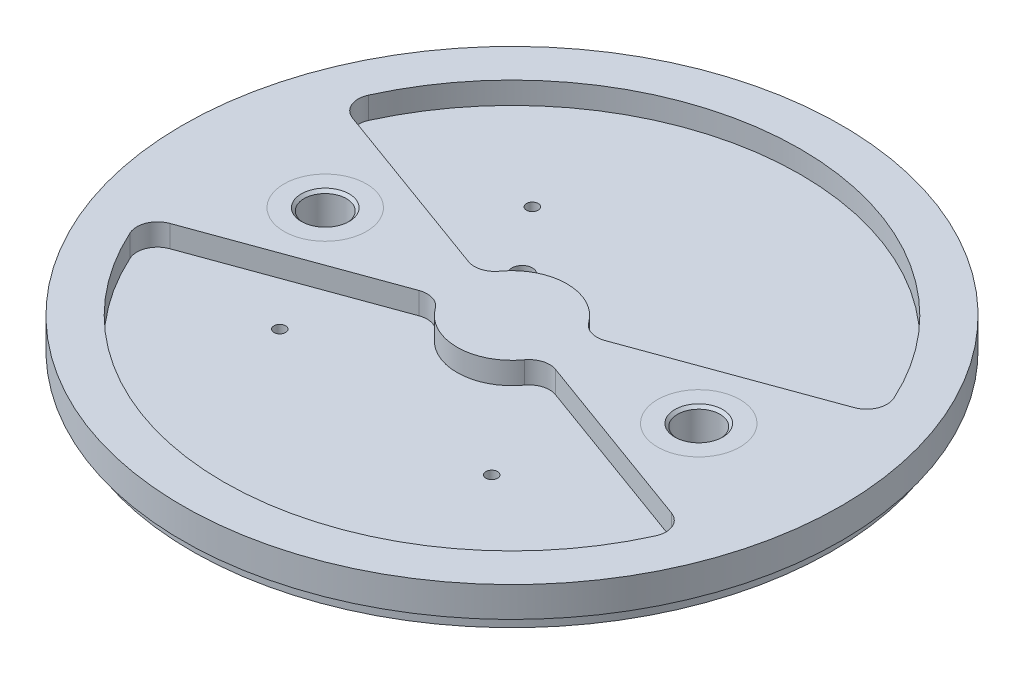
SolidWorks part; units mm, degrees
material "Delrin 2700 NC010, Low Viscosity Acetal Copolymer (SS)"
ref_plane "Front Plane" through (0, 0, 0) normal (0, 0, 1) x (1, 0, 0)
ref_plane "Top Plane" through (0, 0, 0) normal (0, 1, 0) x (1, 0, 0)
ref_plane "Right Plane" through (0, 0, 0) normal (1, 0, 0) x (0, 0, -1)
sketch "Sketch1" plane through (0, 0, 0) normal (0, 1, 0) x (1, 0, 0)
  circle A0 centre (0, 0) radius 76.2
  dimension "D1" = 152.4
extrude "Boss-Extrude1" add sketch "Sketch1" along normal blind 10.16
hole_wizard "Tap Drill for #4-40 Tap1" [suppressed] positions "Sketch3" profile "Sketch4" hole size "#4-40" standard "ANSI Inch"
sketch "Sketch3" plane through (0, 0, 0) normal (0, -1, 0) x (-1, 0, 0)
  point P0 (0, 25.4)
  point P2 (0, 50.4)
  dimension "D1" = 25.4
  dimension "D2" = 25
sketch "Sketch4" plane through (0, 0, -25.4) normal (1, 0, 0) x (0, 0, -1)
  line L0 (0, 0) -> (0, 10.16)
  line L1 (0, 10.16) -> (1.1303, 10.16)
  line L2 (1.1303, 10.16) -> (1.1303, 0)
  line L5 (1.1303, 0) -> (0, 0)
  line L11 (0, -6.35) -> (0, 107.95) construction
  dimension "Thru Hole Dia." = 2.2606
  dimension "Thru Hole Depth" = 10.16
sketch "Sketch2" [suppressed] plane through (0, 0, 0) normal (0, -1, 0) x (1, 0, 0)
  line L0 (0, 0) -> (0, -55.372) construction
  line L1 (-3.429, -27.686) -> (3.429, -27.686)
  line L2 (-5.969, -30.226) -> (-5.969, -45.574)
  line L3 (-3.429, -48.114) -> (3.429, -48.114)
  line L4 (5.969, -30.226) -> (5.969, -45.574)
  arc A0 (3.429, -48.114) -> (5.969, -45.574) centre (3.429, -45.574) ccw
  arc A1 (-5.969, -45.574) -> (-3.429, -48.114) centre (-3.429, -45.574) ccw
  arc A2 (3.429, -27.686) -> (5.969, -30.226) centre (3.429, -30.226) cw
  arc A3 (-3.429, -27.686) -> (-5.969, -30.226) centre (-3.429, -30.226) ccw
  circle A4 centre (0, -25.4) radius 1.1303 construction
  circle A5 centre (0, -50.4) radius 1.1303 construction
  point P10 (5.969, -27.686)
  point P13 (-5.969, -27.686)
  point P17 (0, -27.686)
  dimension "D2" = 2.54
  dimension "D1" = 11.938
  dimension "D3" = 2.286
  dimension "D4" = 2.286
extrude "Cut-Extrude1" [suppressed] cut sketch "Sketch2" against normal through all
hole_wizard "Tap Drill for #6-32 Tap1" positions "Sketch5" profile "Sketch6" hole size "#6-32" standard "ANSI Inch" end condition through all
sketch "Sketch5" plane through (0, 0, 0) normal (0, -1, 0) x (-1, 0, 0)
  line L0 (0, 0) -> (58.3519, 0) construction
  line L2 (0, 0) -> (37.5212, 6.616) construction
  point P0 (37.5212, 6.616)
  dimension "D1" = 10
  dimension "D2" = 38.1
sketch "Sketch6" plane through (-37.5212, 0, -6.616) normal (1, 0, 0) x (0, 0, -1)
  line L0 (0, 0) -> (0, 10.16)
  line L1 (0, 10.16) -> (1.3525, 10.16)
  line L2 (1.3525, 10.16) -> (1.3525, 0)
  line L5 (1.3525, 0) -> (0, 0)
  line L11 (0, -6.35) -> (0, 107.95) construction
  dimension "Thru Hole Dia." = 2.7051
  dimension "Thru Hole Depth" = 10.16
pattern_circular "CirPattern1" count 4 over 360 about axis through (0, 0, 0) along (0, 1, 0) skipping 3 of "Tap Drill for #6-32 Tap1"
hole_wizard "W (0.386) Diameter Hole1" positions "Sketch7" profile "Sketch8" hole size "W" standard "ANSI Inch" end condition through all
sketch "Sketch7" plane through (0, 0, 0) normal (0, -1, 0) x (-1, 0, 0)
  line L2 (0, 0) -> (-33.0778, 27.7556) construction
  line L4 (0, 0) -> (0, 19.4817) construction
  point P0 (-33.0778, 27.7556)
  point P17 (33.0778, -27.7556)
  dimension "D1" = 50
  dimension "D2" = 43.18
  dimension "D3" = 43.18
sketch "Sketch8" plane through (33.0778, 0, -27.7556) normal (1, 0, 0) x (0, 0, -1)
  line L0 (0, 0) -> (0, 10.16)
  line L1 (0, 10.16) -> (4.9022, 10.16)
  line L2 (4.9022, 10.16) -> (4.9022, 0)
  line L5 (4.9022, 0) -> (0, 0)
  line L11 (0, -6.35) -> (0, 107.95) construction
  dimension "Thru Hole Dia." = 9.8044
  dimension "Thru Hole Depth" = 10.16
hole_wizard "3/16 (0.1875) Diameter Hole1" positions "Sketch10" profile "Sketch11" hole size "3/16" standard "ANSI Inch" end condition through all
sketch "Sketch10" plane through (0, 0, 0) normal (0, -1, 0) x (-1, 0, 0)
  line L0 (0, 0) -> (37.5212, 6.616) construction
  point P0 (18.7606, 3.308)
sketch "Sketch11" plane through (-18.7606, 0, -3.308) normal (1, 0, 0) x (0, 0, -1)
  line L0 (0, 0) -> (0, 10.16)
  line L1 (0, 10.16) -> (2.3812, 10.16)
  line L2 (2.3812, 10.16) -> (2.3812, 0)
  line L5 (2.3812, 0) -> (0, 0)
  line L11 (0, -6.35) -> (0, 107.95) construction
  dimension "Thru Hole Dia." = 4.7625
  dimension "Thru Hole Depth" = 10.16
sketch "Sketch12" plane through (0, 0, 0) normal (0, -1, 0) x (1, 0, 0)
  line L0 (0, 0) -> (31.6547, 37.7246) construction
  line L10 (19.8869, 28.7385) -> (24.8486, 24.5751)
  line L11 (19.8869, 28.7385) -> (6.4989, 12.7833)
  line L12 (6.4989, 12.7833) -> (11.4606, 8.62)
  line L13 (24.8486, 24.5751) -> (11.4606, 8.62)
  line L17 (0, 0) -> (-53.1972, 0) construction
  line L18 (-33.0778, 27.7556) -> (33.0778, -27.7556) construction
  circle A0 centre (22.3677, 26.6568) radius 3.2385
  circle A1 centre (8.9797, 10.7016) radius 3.2385
  circle A2 centre (33.0778, -27.7556) radius 4.9022 construction
  circle A3 centre (-33.0778, 27.7556) radius 4.9022 construction
  circle A4 centre (33.0778, -27.7556) radius 4.9022
  circle A5 centre (-33.0778, 27.7556) radius 4.9022
  dimension "D1" = 6.477
  dimension "D2" = 13.97
  dimension "D3" = 20.828
extrude "Cut-Extrude4" cut sketch "Sketch12" against normal blind 3.175 contours A1 L13 A0 L11 | L10 A0 | L12 A1 | L12 A1 | L10 A0
ref_plane "Plane1" through (0, 0, 0) normal (0.6428, 0, 0.766) x (0.766, 0, -0.6428)
mirror "Mirror1" about plane through (0, 0, 0) normal (0.6428, 0, 0.766) of "Cut-Extrude4"
sketch "Sketch15" plane through (0, 0, 0) normal (0, -1, 0) x (1, 0, 0)
  circle A0 centre (0, 0) radius 74.041
  circle A1 centre (0, 0) radius 76.2 construction
  circle A2 centre (0, 0) radius 76.2
  dimension "D1" = 148.082
extrude "Cut-Extrude5" cut sketch "Sketch15" against normal blind 3.175
sketch "Sketch17" plane through (0, 10.16, 0) normal (0, 1, 0) x (1, 0, 0)
  circle A0 centre (-33.0778, -27.7556) radius 9.525
  circle A1 centre (33.0778, 27.7556) radius 9.525
  dimension "D1" = 19.05
  dimension "D2" = 19.05
split line "Split Line1"
sketch "Sketch19" plane through (0, 0, 0) normal (0, -1, 0) x (1, 0, 0)
  circle A0 centre (-33.0778, 27.7556) radius 9.525
  circle A1 centre (33.0778, -27.7556) radius 9.525
  dimension "D1" = 19.05
  dimension "D2" = 19.05
split line "Split Line2"
sketch "Sketch18" plane through (0, 10.16, 0) normal (0, 1, 0) x (1, 0, 0)
  circle A0 centre (0, 0) radius 76.2 construction
  circle A1 centre (33.0778, 27.7556) radius 9.525 construction
  circle A2 centre (-33.0778, -27.7556) radius 9.525 construction
  circle A3 centre (0, 0) radius 76.2
  circle A4 centre (33.0778, 27.7556) radius 9.525
  circle A5 centre (-33.0778, -27.7556) radius 9.525
  circle A7 centre (0, 0) radius 12.7
  circle A8 centre (-18.7606, 3.308) radius 9.525
  dimension "D1" = 25.4
  dimension "D2" = 19.05
extrude "Cut-Extrude6" [suppressed] cut sketch "Sketch18" against normal blind 4.7625
sketch "Sketch20" plane through (0, 10.16, 0) normal (0, 1, 0) x (1, 0, 0)
  line L0 (-5.3508, -4.4899) -> (5.3508, 4.4899) construction
  line L1 (11.9341, 4.3437) -> (62.654, 22.8042)
  line L2 (0, 0) -> (-85.2847, -31.0411) construction
  line L3 (0, 0) -> (40.2406, 69.6988) construction
  line L4 (0, 0) -> (-109.7287, 0) construction
  line L5 (6.35, 10.9985) -> (33.3375, 57.7422)
  line L6 (-62.654, -22.8042) -> (-11.9341, -4.3437)
  line L7 (-33.3375, -57.7422) -> (-6.35, -10.9985)
  circle A0 centre (0, 0) radius 66.675
  circle A1 centre (0, 0) radius 12.7
  circle A2 centre (-59.6352, -16.6373) radius 4.7625
  circle A4 centre (26.7401, 55.8402) radius 4.7625
  circle A7 centre (4.2758, 16.9309) radius 4.7625
  circle A8 centre (-17.4162, -1.2708) radius 4.7625
  circle A9 centre (-4.2758, -16.9309) radius 4.7625
  circle A10 centre (17.4162, 1.2708) radius 4.7625
  circle A11 centre (59.6352, 16.6373) radius 4.7625
  circle A12 centre (-26.7401, -55.8402) radius 4.7625
  dimension "D1" = 133.35
  dimension "D2" = 25.4
  dimension "D4" = 9.525
  dimension "D3" = 20
  dimension "D5" = 140
extrude "Cut-Extrude7" cut sketch "Sketch20" against normal blind 5.08
move or copy body "Body-Move/Copy1" bodies to move or copy 115 copy no rotation origin (0, 0, 0) rotation axis (0, -1, 0) rotation angle 40
chamfer "Chamfer1" distance 0.635 angle 45 4 edges at (46.3311, 0, -3.7553) (-40.0289, 0, -3.7553) (46.3311, 10.16, -3.7553) (-40.0289, 10.16, -3.7553)
equation "\"Bodytube_OD\" = 6.17in"
equation "\"Bodytube_ID\" = 5.998in"
equation "\"Camera_Cutout_Width\"=10mm"
equation "\"Camera_Cutout_Height\"=7mm"
equation "\"Fwd_Tube_Length\" = 38.5in"
equation "\"BKHD_Screw_Diam\"= 3.5mm"
equation "\"Fwd_BKHD_From_Top\" = 18in"
equation "\"Shear_Screw_Diameter\" = 0.086in"
equation "\"Shear_Screw_Coupler_Location\" = 4.5in"
equation "\"Motor_OD\" = 4in"
equation "\"Mid_Coupler_Length\" = 13in"
equation "\"Aft_Section_Length\"= 36in"
equation "\"AB_Coupler_OD_Length\"= 1in"
equation "\"AB_Coupling_Section_Length\"= 0.375in"
equation "\"AB_Coupler_Length\"= \"AB_Coupler_OD_Length\" + \"AB_Coupling_Section_Length\" * 2"
equation "\"Cutout_Angle\" = 80"
equation "\"AB_Paddle_Height\" = 0.375in"
equation "\"AB_Coupler_Num_Screws\"= 4"
equation "\"AB_BKHD_Thickness\" = 0.375in"
equation "\"AB_Mount_From_Bottom\" = 23.175in"
equation "\"Num_Cutouts\" = 3"
equation "\"AB_Coupler_OD\"= 6.17in"
equation "\"AB_Coupler_ID\"= 5.75in"
equation "\"AB_Coupler_Surface_Diameter\"= 5.998in"
equation "\"AB_Coupling_Screw_Diameter\"= 0.15748in"
equation "\"AB_Central_Bushing_Length\" = .4724in"
equation "\"Lead_Screw_Dist\" = 3.4in"
equation "\"Lead_Screw_Diam\" = 0.386in"
equation "\"Lead_Screw_Length\" = (\"Mid_Coupler_Length\" + 2*0.375in + 2*.75in)"
equation "\"Paddle_Pin_Offset\" = .25in"
equation "\"Paddle_Pin_Radius\" = 2.25in"
equation "\"SS_Paddle_Pin_Radius\" = 2.25*0.66in"
equation "\"Paddle_Gear_OD\" = 3.2in"
equation "\"Drive_Gear_OD\" = 1.7in"
equation "\"Fin_Thickness\"= .118in"
equation "\"Guiderail_Cutout_Diameter\"= 1.5in"
equation "\"DB9_Hole_Dist\" = 25mm"
equation "\"DB9_Relief_Width\" = 0.47in"
equation "\"DB9_Relief_Hole_Offset\" = 0.09in"
equation "\"Airbrakes_Wire_Hole_Dia\" = .25in"
equation "\"Airbrakes_Wire_Hole_Dist\" = 1.1in"
equation "\"Servo_Gear_Offset\" = 0.5in"
equation "\"FWD_Shear_Screw_Dist\" = 1.5in"
equation "\"Camera_Screw_Dia\" = 0.216535"
equation "\"Camera_Hole_Angle\" = atn ( 2 / 3 * tan ( 12.5deg ) )"
equation "\"Coupler_OD\" = 5.998"
equation "\"Coupler_ID\" = 5.8"
equation "\"Mounting_Bracket_Centerhole_DIA\" = 0.4in"
equation "\"Drive_Gear_Shaft_DIA\" = \"Mounting_Bracket_Centerhole_DIA\" - 0.02in"
equation "\"Drive_Gear_Fillet\" = 0.22in"
equation "\"Drive_Gear_ID\" = 0.62in"
equation "\"Drive_Gear_Offset\" = 0.01in"
equation "\"D1@Sketch2\"=\"DB9_Relief_Width\""
equation "\"D2@Sketch3\"=\"DB9_Hole_Dist\""
equation "\"D3@Sketch2\"=\"DB9_Relief_Hole_Offset\""
equation "\"D4@Sketch2\"=\"DB9_Relief_Hole_Offset\""
equation "\"D2@Sketch7\"=\"Lead_Screw_Dist\"/2"
equation "\"D3@Sketch7\"=\"Lead_Screw_Dist\"/2"
